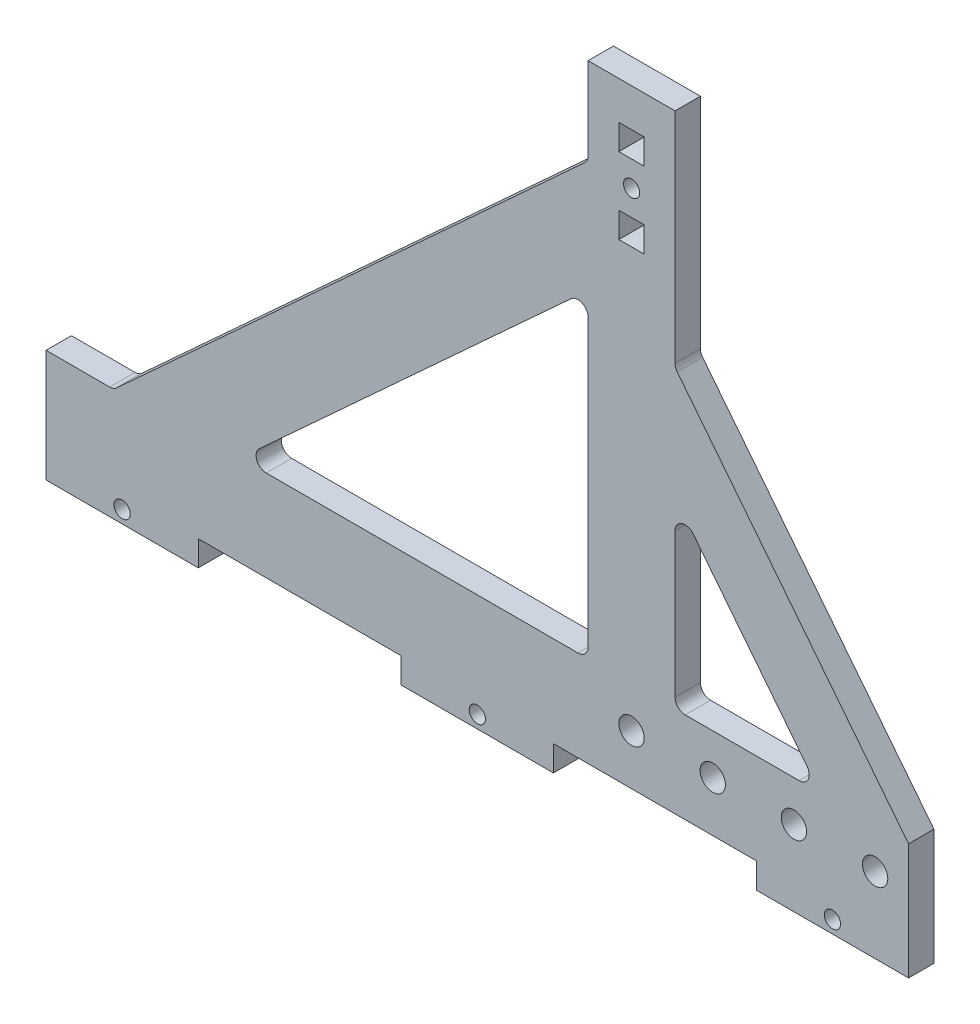
SolidWorks part; units mm, degrees
ref_plane "Front Plane" through (0, 0, 0) normal (0, 0, 1) x (1, 0, 0)
ref_plane "Top Plane" through (0, 0, 0) normal (0, 1, 0) x (1, 0, 0)
ref_plane "Right Plane" through (0, 0, 0) normal (1, 0, 0) x (0, 0, -1)
sketch "Sketch1" plane through (0, 0, 0) normal (0, 0, 1) x (1, 0, 0)
  line L4 (21.7678, 129.6673) -> (0, 129.6673)
  line L5 (0, 129.6673) -> (0, 109.0169)
  line L8 (-97.5764, -22.7327) -> (-46.7764, -22.7327)
  line L11 (80.2236, 0) -> (22.3142, 73.3492)
  line L14 (21.7678, 129.6673) -> (21.7678, 74.9232)
  line L17 (-135.6764, -0.9649) -> (-119.7586, -0.9649)
  line L18 (-118.0423, -0.2973) -> (-0.8237, 107.1445)
  line L19 (-135.6764, -29.0827) -> (-97.5764, -29.0827)
  line L20 (24.3078, 0) -> (52.8229, 0)
  line L21 (54.8164, 4.1139) -> (26.3014, 40.2317)
  line L22 (21.7678, 38.6578) -> (21.7678, 2.54)
  line L23 (-97.5764, -29.0827) -> (-97.5764, -22.7327)
  line L24 (0, 2.54) -> (0, 74.0585)
  line L25 (-4.2563, 75.9309) -> (-82.2826, 4.4124)
  line L26 (-80.5664, 0) -> (-2.54, 0)
  line L28 (80.2236, -29.0827) -> (42.1236, -29.0827)
  line L29 (42.1236, -29.0827) -> (42.1236, -22.7327)
  line L30 (-46.7764, -22.7327) -> (-46.7764, -29.0827)
  line L31 (-46.7764, -29.0827) -> (-8.6764, -29.0827)
  line L32 (-8.6764, -29.0827) -> (-8.6764, -22.7327)
  line L33 (-8.6764, -22.7327) -> (42.1236, -22.7327)
  line L34 (-135.6764, -0.9649) -> (-135.6764, -29.0827)
  line L35 (80.2236, 0) -> (80.2236, -29.0827)
  line L37 (7.7089, 113.7923) -> (14.0589, 113.7923)
  line L38 (7.7089, 113.7923) -> (7.7089, 120.1423)
  line L39 (7.7089, 120.1423) -> (14.0589, 120.1423)
  line L40 (14.0589, 113.7923) -> (14.0589, 120.1423)
  line L41 (7.7089, 113.7923) -> (14.0589, 120.1423) construction
  line L42 (7.7089, 120.1423) -> (14.0589, 113.7923) construction
  line L43 (7.7089, 94.7423) -> (14.0589, 94.7423)
  line L44 (7.7089, 94.7423) -> (7.7089, 101.0923)
  line L45 (7.7089, 101.0923) -> (14.0589, 101.0923)
  line L46 (14.0589, 94.7423) -> (14.0589, 101.0923)
  line L47 (7.7089, 94.7423) -> (14.0589, 101.0923) construction
  line L48 (7.7089, 101.0923) -> (14.0589, 94.7423) construction
  arc A0 (52.8229, 0) -> (54.8164, 4.1139) centre (52.8229, 2.54) ccw
  arc A1 (26.3014, 40.2317) -> (21.7678, 38.6578) centre (24.3078, 38.6578) ccw
  arc A2 (21.7678, 2.54) -> (24.3078, 0) centre (24.3078, 2.54) ccw
  arc A3 (-82.2826, 4.4124) -> (-80.5664, 0) centre (-80.5664, 2.54) ccw
  arc A4 (-2.54, 0) -> (0, 2.54) centre (-2.54, 2.54) ccw
  arc A5 (0, 74.0585) -> (-4.2563, 75.9309) centre (-2.54, 74.0585) ccw
  arc A6 (-119.7586, -0.9649) -> (-118.0423, -0.2973) centre (-119.7586, 1.5751) ccw
  arc A7 (0, 109.0169) -> (-0.8237, 107.1445) centre (-2.54, 109.0169) cw
  arc A8 (22.3142, 73.3492) -> (21.7678, 74.9232) centre (24.3078, 74.9232) cw
  circle A9 centre (-116.6264, -25.9077) radius 2.032
  circle A10 centre (-27.7264, -25.9077) radius 2.032
  circle A11 centre (61.1736, -25.9077) radius 2.032
  circle A12 centre (10.8839, 107.4423) radius 2.032
  point P18 (58.0644, 0)
  point P23 (21.7678, 45.974)
  point P26 (21.7678, 0)
  point P29 (-87.0966, 0)
  point P32 (0, 0)
  point P35 (0, 79.8322)
  point P39 (-118.7706, -0.9649)
  point P42 (0, 107.8995)
  point P45 (21.7678, 74.0413)
  point P53 (10.8839, 116.9673)
  point P55 (-97.5764, -25.9077)
  point P56 (-116.6264, -29.0827)
  point P61 (-27.7264, -29.0827)
  point P62 (-8.6764, -25.9077)
  point P67 (42.1236, -25.9077)
  point P68 (61.1736, -29.0827)
  point P70 (10.8839, 129.6673)
  point P72 (10.8839, 97.9173)
  dimension "D15" = 2.54
  dimension "D16" = 2.54
  dimension "D4" = 4.064
  dimension "D17" = 4.064
  dimension "D24" = 4.064
  dimension "D25" = 4.064
  dimension "D2" = 152.4
  dimension "D3" = 6.35
  dimension "D5" = 94.3356
  dimension "D6" = 55.626
  dimension "D7" = 21.7678
  dimension "D8" = 21.7678
  dimension "D9" = 21.7678
  dimension "D10" = 36.2966
  dimension "D11" = 45.974
  dimension "D12" = 79.8322
  dimension "D13" = 87.0966
  dimension "D14" = 21.7678
  dimension "D18" = 38.1
  dimension "D19" = 6.35
  dimension "D20" = 6.35
  dimension "D21" = 12.7
  dimension "D22" = 19.05
  dimension "D23" = 9.525
  dimension "D26" = 215.9
extrude "Boss-Extrude2" add sketch "Sketch1" along normal blind 6.35
sketch "Sketch3" plane through (0, 0, 6.35) normal (0, 0, 1) x (1, 0, 0)
  line L0 (80.2236, -10.16) -> (0, -10.16) construction
  line L1 (80.2236, 0) -> (80.2236, -29.0827) construction
  line L2 (21.7678, 129.6673) -> (0, 129.6673) construction
  circle A2 centre (10.8839, -10.16) radius 3.175
  circle A6 centre (31.2039, -10.16) radius 3.175
  circle A7 centre (51.5239, -10.16) radius 3.175
  circle A8 centre (71.8439, -10.16) radius 3.175
  point P21 (10.8839, 129.6673)
  dimension "D3" = 6.35
  dimension "D4" = 20.32
  dimension "D1" = 10.16
  dimension "D2" = 4
extrude "Cut-Extrude1" cut sketch "Sketch3" along normal through all from surface at -6.35 starting at face at (12.9159, 107.4423, 0)
